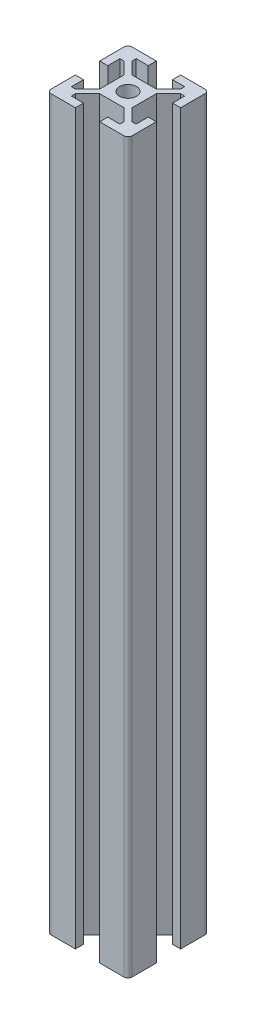
SolidWorks part; units mm, degrees
ref_plane "Front Plane" through (0, 0, 0) normal (0, 0, 1) x (1, 0, 0)
ref_plane "Top Plane" through (0, 0, 0) normal (0, 1, 0) x (1, 0, 0)
ref_plane "Right Plane" through (0, 0, 0) normal (1, 0, 0) x (0, 0, -1)
sketch "Sketch1" plane through (0, 0, 0) normal (0, 1, 0) x (1, 0, 0)
  line L5 (-3, 10) -> (-10, 10)
  line L6 (-4, 3) -> (-7, 6)
  line L7 (-4, -4) -> (4, -4)
  line L8 (-4, -4) -> (-4, 4)
  line L9 (-4, 4) -> (4, 4)
  line L10 (4, -4) -> (4, 4)
  line L11 (-8, 6) -> (-7, 6)
  line L12 (-8, 6) -> (-8, 3)
  line L16 (-3, 8) -> (-3, 10)
  line L21 (-8, 3) -> (-10, 3)
  line L22 (-6, 8) -> (-6, 7)
  line L23 (-10, 3) -> (-10, 10)
  line L24 (-3, 4) -> (-6, 7)
  line L25 (3, 10) -> (10, 10)
  line L26 (6, 8) -> (3, 8)
  line L27 (-6, 8) -> (-3, 8)
  line L28 (3, 8) -> (3, 10)
  line L29 (-10, 10) -> (-4, 4)
  line L30 (6, 8) -> (6, 7)
  line L31 (3, 4) -> (6, 7)
  line L32 (4, 3) -> (7, 6)
  line L33 (8, 6) -> (7, 6)
  line L34 (8, 6) -> (8, 3)
  line L35 (8, 3) -> (10, 3)
  line L36 (10, 3) -> (10, 10)
  line L37 (10, -3) -> (10, -10)
  line L38 (8, -6) -> (8, -3)
  line L39 (8, -3) -> (10, -3)
  line L40 (8, -6) -> (7, -6)
  line L41 (4, -3) -> (7, -6)
  line L42 (3, -4) -> (6, -7)
  line L43 (6, -8) -> (6, -7)
  line L44 (6, -8) -> (3, -8)
  line L45 (3, -8) -> (3, -10)
  line L46 (3, -10) -> (10, -10)
  line L47 (-3, -10) -> (-10, -10)
  line L48 (-6, -8) -> (-3, -8)
  line L49 (-3, -8) -> (-3, -10)
  line L50 (-6, -8) -> (-6, -7)
  line L51 (-3, -4) -> (-6, -7)
  line L52 (-4, -3) -> (-7, -6)
  line L53 (-8, -6) -> (-7, -6)
  line L54 (-8, -6) -> (-8, -3)
  line L55 (-8, -3) -> (-10, -3)
  line L56 (-10, -3) -> (-10, -10)
  circle A0 centre (0, 0) radius 2.1
  point P0 (0, 0)
  point P55 (0, 0)
  dimension "D3" = 3
  dimension "D1" = 4.2
  dimension "D2" = 4
  dimension "D4" = 4
  dimension "D5" = 6
  dimension "D7" = 8
  dimension "D8" = 10
  dimension "D6" = 4
extrude "Boss-Extrude1" add sketch "Sketch1" along normal blind 180 contours L29 L23 L21 L12 L11 L6 L8 | L5 L29 L9 L24 L22 L27 L16 | L35 L36 L25 L28 L26 L30 L31 L9 L10 L32 L33 L34 | L7 L10 L9 L8 A0 | L45 L46 L37 L39 L38 L40 L41 L10 L7 L42 L43 L44 | L55 L56 L47 L49 L48 L50 L51 L7 L8 L52 L53 L54
fillet "Fillet1" radius 1 4 edges at (-10, 90, 10) (-10, 90, -10) (10, 90, -10) (10, 90, 10)
